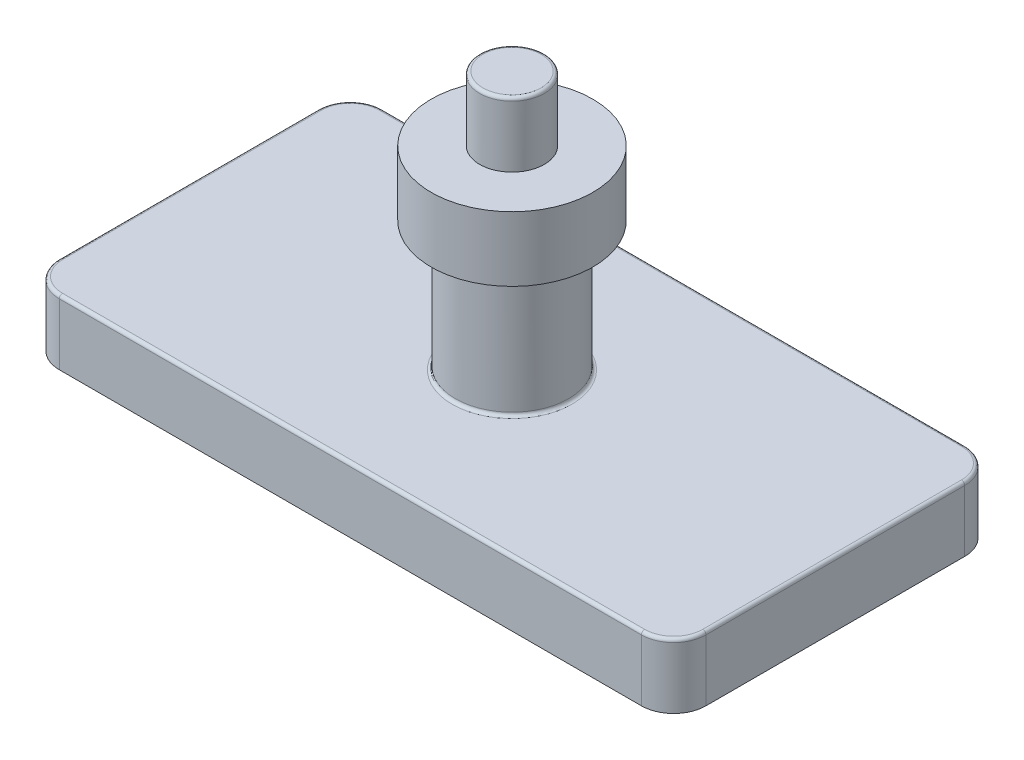
SolidWorks part; units mm, degrees
ref_plane "Front Plane" through (0, 0, 0) normal (0, 0, 1) x (1, 0, 0)
ref_plane "Top Plane" through (0, 0, 0) normal (0, 1, 0) x (1, 0, 0)
ref_plane "Right Plane" through (0, 0, 0) normal (1, 0, 0) x (0, 0, -1)
sketch "Sketch1" plane through (0, 0, 0) normal (0, 1, 0) x (1, 0, 0)
  line L0 (-127, 63.5) -> (127, -63.5) construction
  line L1 (-127, 63.5) -> (127, 63.5)
  line L2 (-127, 63.5) -> (-127, -63.5)
  line L3 (-127, -63.5) -> (127, -63.5)
  line L4 (127, 63.5) -> (127, -63.5)
  dimension "D1" = 254
  dimension "D2" = 127
extrude "Extrude1" add sketch "Sketch1" along normal blind 25.4
sketch "Sketch3" plane through (0, 0, 0) normal (0, 0, 1) x (1, 0, 0)
  line L0 (0, 0) -> (0, 120.1827) construction
  line L1 (0, 127) -> (12.7, 127)
  line L2 (12.7, 127) -> (12.7, 101.6)
  line L3 (12.7, 101.6) -> (31.75, 101.6)
  line L4 (31.75, 101.6) -> (31.75, 76.2)
  line L5 (31.75, 76.2) -> (22.225, 76.2)
  line L6 (22.225, 76.2) -> (22.225, 25.4)
  line L7 (-127, 25.4) -> (127, 25.4) construction
  line L8 (22.225, 25.4) -> (0, 25.4)
  line L9 (0, 127) -> (0, 25.4)
  dimension "D1" = 25.4
  dimension "D2" = 63.5
  dimension "D3" = 44.45
  dimension "D4" = 50.8
  dimension "D5" = 76.2
  dimension "D6" = 101.6
revolve "Revolve1" add sketch "Sketch3" angle 360 about L0
fillet "Fillet1" radius 12.7 4 edges at (127, 12.7, 63.5) (127, 12.7, -63.5) (-127, 12.7, -63.5) (-127, 12.7, 63.5)
fillet "Fillet2" radius 1.27 10 edges at (-123.2803, 25.4, 59.7803) (-127, 25.4, 0) (-123.2803, 25.4, -59.7803) (0, 25.4, -63.5) (123.2803, 25.4, -59.7803) (127, 25.4, 0) (123.2803, 25.4, 59.7803) (0, 25.4, 22.225) (0, 25.4, 63.5) (0, 127, -12.7)
